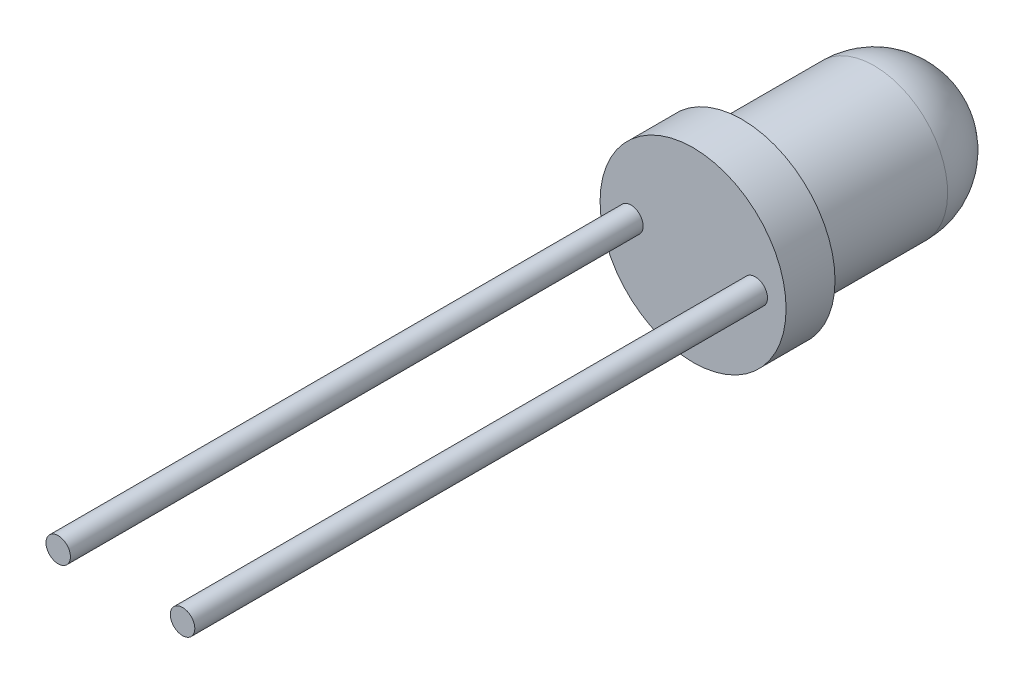
SolidWorks part; units mm, degrees
ref_plane "前视基准面" through (0, 0, 0) normal (0, 0, 1) x (1, 0, 0)
ref_plane "上视基准面" through (0, 0, 0) normal (0, 1, 0) x (1, 0, 0)
ref_plane "右视基准面" through (0, 0, 0) normal (1, 0, 0) x (0, 0, -1)
sketch "草图1" plane through (0, 0, 0) normal (0, 0, 1) x (1, 0, 0)
  circle A0 centre (0, 0) radius 1.5
  dimension "D1" = 3
extrude "拉伸1" add sketch "草图1" along normal blind 3.7
sketch "草图2" plane through (0, 0, 3.7) normal (0, 0, 1) x (1, 0, 0)
  circle A0 centre (0, 0) radius 1.9
  dimension "D1" = 3.8
extrude "拉伸2" add sketch "草图2" against normal blind 1
sketch "草图3" plane through (0, 0, 2.7) normal (0, 0, -1) x (-1, 0, 0)
  line L0 (0, 2.011) -> (0, -2.1052) construction
  line L1 (-2.1813, 0) -> (2.3335, 0) construction
  circle A0 centre (-1.27, 0) radius 0.25
  circle A1 centre (1.27, 0) radius 0.25
  dimension "D1" = 0.5
  dimension "D2" = 2.54
extrude "拉伸3" add sketch "草图3" against normal blind 12.7
sketch "草图5" plane through (0, 0, 0) normal (1, 0, 0) x (0, 0, -1)
  line L0 (0, 1.5) -> (0, 0)
  line L1 (1.5, 0) -> (0, 0)
  arc A0 (0, 1.5) -> (1.5, 0) centre (0, 0) cw
  dimension "D1" = 1.5
revolve "旋转2" add sketch "草图5" angle 360 about L1
